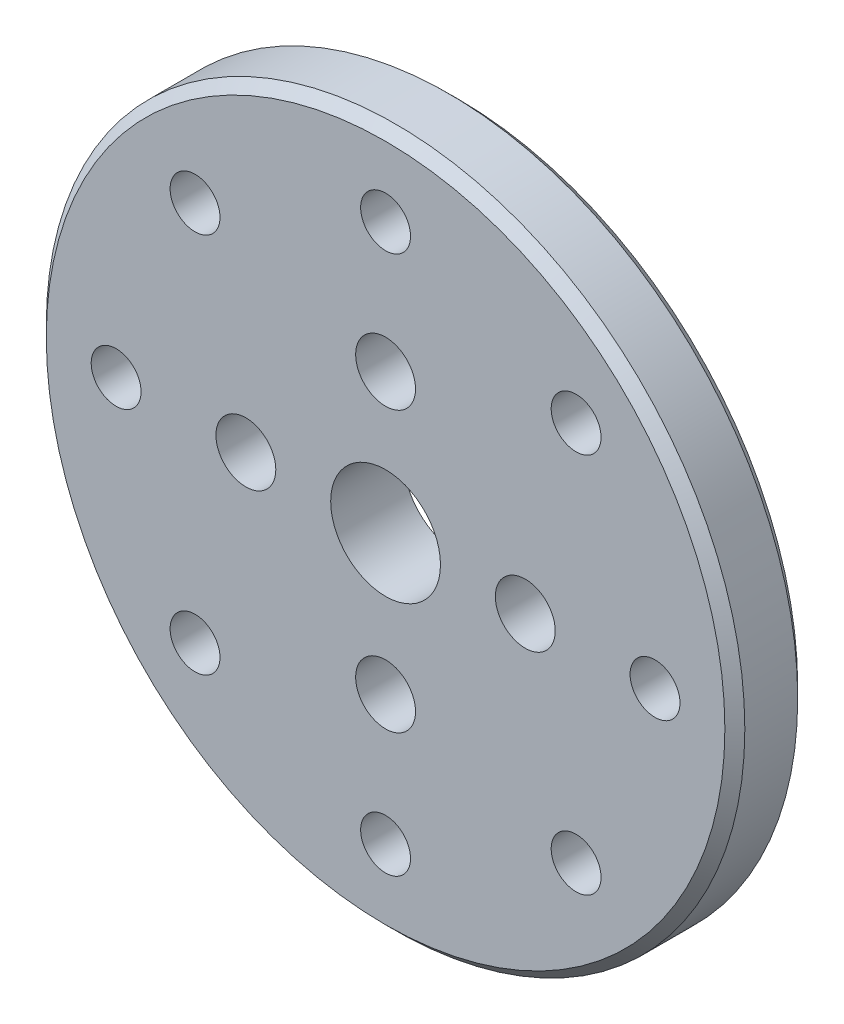
SolidWorks part; units mm, degrees
ref_plane "前视基准面" through (0, 0, 0) normal (0, 0, 1) x (1, 0, 0)
ref_plane "上视基准面" through (0, 0, 0) normal (0, 1, 0) x (1, 0, 0)
ref_plane "右视基准面" through (0, 0, 0) normal (1, 0, 0) x (0, 0, -1)
other "Configuration Table"
sketch "草图1" plane through (0, 0, 0) normal (0, 0, 1) x (1, 0, 0)
  circle A0 centre (0, 0) radius 17.5
  dimension "D1" = 35
extrude "凸台-拉伸1" add sketch "草图1" along normal blind 3.65
sketch "草图3" plane through (0, 0, 0) normal (0, 0, -1) x (-1, 0, 0)
  circle A0 centre (0, 0) radius 13.5 construction
  circle A1 centre (0, 13.5) radius 1.25
  circle A2 centre (9.5459, 9.5459) radius 1.25
  circle A3 centre (13.5, 0) radius 1.25
  circle A4 centre (9.5459, -9.5459) radius 1.25
  circle A5 centre (0, -13.5) radius 1.25
  circle A6 centre (-9.5459, -9.5459) radius 1.25
  circle A7 centre (-13.5, 0) radius 1.25
  circle A8 centre (-9.5459, 9.5459) radius 1.25
  point P21 (0, 0)
  dimension "D1" = 27
  dimension "D2" = 2.5
  dimension "D3" = 8
extrude "切除-拉伸1" cut sketch "草图3" against normal blind 5
chamfer "倒角1" distance 0.5 angle 45 2 edges at (17.5, 0, 0) (17.5, 0, 3.65)
sketch "草图4" plane through (0, 0, 0) normal (0, 0, -1) x (-1, 0, 0)
  circle A0 centre (0, 0) radius 7 construction
  circle A1 centre (0, 7) radius 1.5
  circle A2 centre (7, 0) radius 1.5
  circle A3 centre (0, -7) radius 1.5
  circle A4 centre (-7, 0) radius 1.5
  point P14 (0, 0)
  dimension "D1" = 14
  dimension "D2" = 3
  dimension "D3" = 4
extrude "切除-拉伸2" cut sketch "草图4" against normal blind 10
sketch "草图5" plane through (0, 0, 0) normal (0, 0, -1) x (-1, 0, 0)
  circle A0 centre (0, 0) radius 2.75
  dimension "D1" = 5.5
extrude "切除-拉伸3" cut sketch "草图5" against normal blind 10
